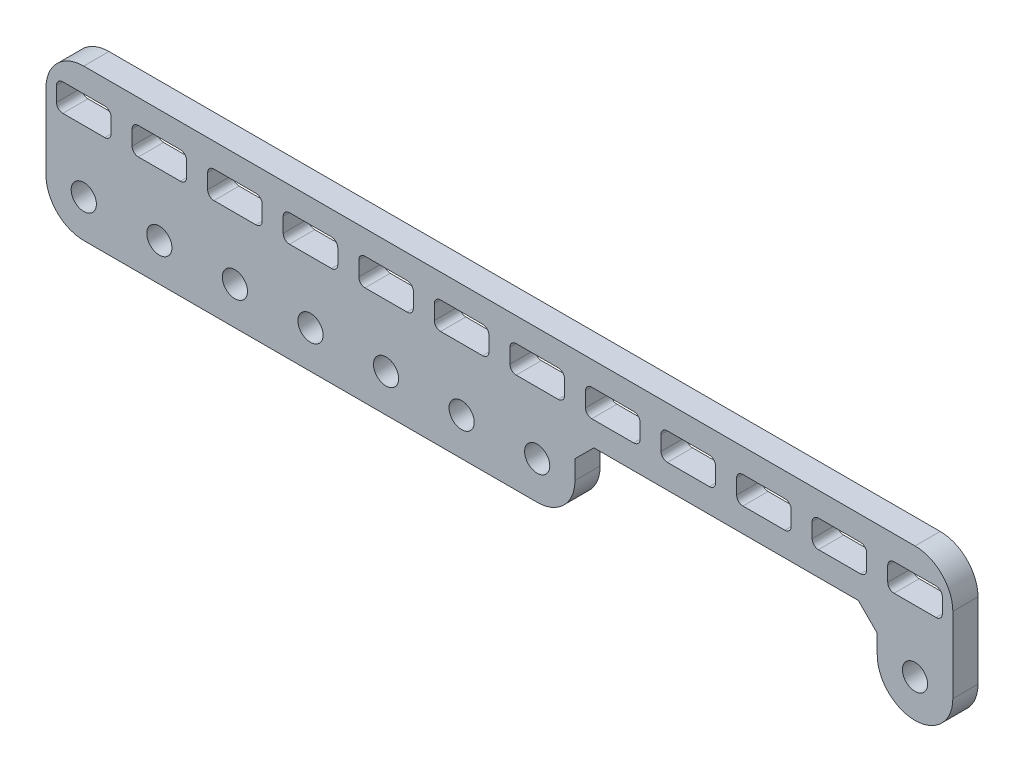
SolidWorks part; units mm, degrees
ref_plane "Alzado" through (0, 0, 0) normal (0, 0, 1) x (1, 0, 0)
ref_plane "Planta" through (0, 0, 0) normal (0, 1, 0) x (1, 0, 0)
ref_plane "Vista lateral" through (0, 0, 0) normal (1, 0, 0) x (0, 0, -1)
sketch "Model" plane through (0, 0, 0) normal (0, 0, 1) x (1, 0, 0)
  line L0 (256.4291, 228.7422) -> (355.4291, 228.7422)
  line L1 (310.4291, 210.7422) -> (256.4291, 210.7422)
  line L2 (359.9291, 224.2422) -> (359.9291, 215.2422)
  line L3 (251.9291, 224.2422) -> (251.9291, 215.2422)
  line L4 (267.9291, 222.6172) -> (262.9291, 222.6172)
  line L5 (262.1791, 223.3672) -> (262.1791, 225.1172)
  line L6 (262.9291, 225.8672) -> (267.9291, 225.8672)
  line L7 (268.6791, 225.1172) -> (268.6791, 223.3672)
  line L8 (285.9291, 222.6172) -> (280.9291, 222.6172)
  line L9 (280.1791, 223.3672) -> (280.1791, 225.1172)
  line L10 (280.9291, 225.8672) -> (285.9291, 225.8672)
  line L11 (286.6791, 225.1172) -> (286.6791, 223.3672)
  line L12 (258.9291, 222.6172) -> (253.9291, 222.6172)
  line L13 (253.1791, 223.3672) -> (253.1791, 225.1172)
  line L14 (253.9291, 225.8672) -> (258.9291, 225.8672)
  line L15 (259.6791, 225.1172) -> (259.6791, 223.3672)
  line L16 (276.9291, 222.6172) -> (271.9291, 222.6172)
  line L17 (271.1791, 223.3672) -> (271.1791, 225.1172)
  line L18 (271.9291, 225.8672) -> (276.9291, 225.8672)
  line L19 (277.6791, 225.1172) -> (277.6791, 223.3672)
  line L20 (294.9291, 222.6172) -> (289.9291, 222.6172)
  line L21 (289.1791, 223.3672) -> (289.1791, 225.1172)
  line L22 (289.9291, 225.8672) -> (294.9291, 225.8672)
  line L23 (295.6791, 225.1172) -> (295.6791, 223.3672)
  line L24 (303.9291, 222.6172) -> (298.9291, 222.6172)
  line L25 (298.1791, 223.3672) -> (298.1791, 225.1172)
  line L26 (298.9291, 225.8672) -> (303.9291, 225.8672)
  line L27 (304.6791, 225.1172) -> (304.6791, 223.3672)
  line L28 (321.9291, 222.6172) -> (316.9291, 222.6172)
  line L29 (316.1791, 223.3672) -> (316.1791, 225.1172)
  line L30 (316.9291, 225.8672) -> (321.9291, 225.8672)
  line L31 (322.6791, 225.1172) -> (322.6791, 223.3672)
  line L32 (312.9291, 222.6172) -> (307.9291, 222.6172)
  line L33 (307.1791, 223.3672) -> (307.1791, 225.1172)
  line L34 (307.9291, 225.8672) -> (312.9291, 225.8672)
  line L35 (313.6791, 225.1172) -> (313.6791, 223.3672)
  line L36 (357.9291, 222.6172) -> (352.9291, 222.6172)
  line L37 (352.1791, 223.3672) -> (352.1791, 225.1172)
  line L38 (352.9291, 225.8672) -> (357.9291, 225.8672)
  line L39 (358.6791, 225.1172) -> (358.6791, 223.3672)
  line L40 (348.9291, 222.6172) -> (343.9291, 222.6172)
  line L41 (343.1791, 223.3672) -> (343.1791, 225.1172)
  line L42 (343.9291, 225.8672) -> (348.9291, 225.8672)
  line L43 (349.6791, 225.1172) -> (349.6791, 223.3672)
  line L44 (339.9291, 222.6172) -> (334.9291, 222.6172)
  line L45 (334.1791, 223.3672) -> (334.1791, 225.1172)
  line L46 (334.9291, 225.8672) -> (339.9291, 225.8672)
  line L47 (340.6791, 225.1172) -> (340.6791, 223.3672)
  line L48 (330.9291, 222.6172) -> (325.9291, 222.6172)
  line L49 (325.1791, 223.3672) -> (325.1791, 225.1172)
  line L50 (325.9291, 225.8672) -> (330.9291, 225.8672)
  line L51 (331.6791, 225.1172) -> (331.6791, 223.3672)
  line L52 (317.1791, 219.7422) -> (348.6791, 219.7422)
  line L53 (314.9291, 215.2422) -> (314.9291, 217.4922)
  line L54 (350.9291, 215.2422) -> (350.9291, 217.4922)
  line L55 (350.9291, 217.4922) -> (348.6791, 219.7422)
  line L56 (314.9291, 217.4922) -> (317.1791, 219.7422)
  arc A0 (359.9291, 224.2422) -> (355.4291, 228.7422) centre (355.4291, 224.2422) ccw
  arc A1 (256.4291, 228.7422) -> (251.9291, 224.2422) centre (256.4291, 224.2422) ccw
  arc A2 (251.9291, 215.2422) -> (256.4291, 210.7422) centre (256.4291, 215.2422) ccw
  circle A3 centre (310.4291, 215.2422) radius 1.5
  circle A4 centre (292.4291, 215.2422) radius 1.5
  circle A5 centre (301.4291, 215.2422) radius 1.5
  circle A6 centre (274.4291, 215.2422) radius 1.5
  circle A7 centre (283.4291, 215.2422) radius 1.5
  circle A8 centre (265.4291, 215.2422) radius 1.5
  circle A9 centre (256.4291, 215.2422) radius 1.5
  circle A10 centre (355.4291, 215.2422) radius 1.5
  arc A11 (262.1791, 223.3672) -> (262.9291, 222.6172) centre (262.9291, 223.3672) ccw
  arc A12 (262.9291, 225.8672) -> (262.1791, 225.1172) centre (262.9291, 225.1172) ccw
  arc A13 (268.6791, 225.1172) -> (267.9291, 225.8672) centre (267.9291, 225.1172) ccw
  arc A14 (267.9291, 222.6172) -> (268.6791, 223.3672) centre (267.9291, 223.3672) ccw
  arc A15 (280.1791, 223.3672) -> (280.9291, 222.6172) centre (280.9291, 223.3672) ccw
  arc A16 (280.9291, 225.8672) -> (280.1791, 225.1172) centre (280.9291, 225.1172) ccw
  arc A17 (286.6791, 225.1172) -> (285.9291, 225.8672) centre (285.9291, 225.1172) ccw
  arc A18 (285.9291, 222.6172) -> (286.6791, 223.3672) centre (285.9291, 223.3672) ccw
  arc A19 (253.1791, 223.3672) -> (253.9291, 222.6172) centre (253.9291, 223.3672) ccw
  arc A20 (253.9291, 225.8672) -> (253.1791, 225.1172) centre (253.9291, 225.1172) ccw
  arc A21 (259.6791, 225.1172) -> (258.9291, 225.8672) centre (258.9291, 225.1172) ccw
  arc A22 (258.9291, 222.6172) -> (259.6791, 223.3672) centre (258.9291, 223.3672) ccw
  arc A23 (271.1791, 223.3672) -> (271.9291, 222.6172) centre (271.9291, 223.3672) ccw
  arc A24 (271.9291, 225.8672) -> (271.1791, 225.1172) centre (271.9291, 225.1172) ccw
  arc A25 (277.6791, 225.1172) -> (276.9291, 225.8672) centre (276.9291, 225.1172) ccw
  arc A26 (276.9291, 222.6172) -> (277.6791, 223.3672) centre (276.9291, 223.3672) ccw
  arc A27 (289.1791, 223.3672) -> (289.9291, 222.6172) centre (289.9291, 223.3672) ccw
  arc A28 (289.9291, 225.8672) -> (289.1791, 225.1172) centre (289.9291, 225.1172) ccw
  arc A29 (295.6791, 225.1172) -> (294.9291, 225.8672) centre (294.9291, 225.1172) ccw
  arc A30 (294.9291, 222.6172) -> (295.6791, 223.3672) centre (294.9291, 223.3672) ccw
  arc A31 (298.1791, 223.3672) -> (298.9291, 222.6172) centre (298.9291, 223.3672) ccw
  arc A32 (298.9291, 225.8672) -> (298.1791, 225.1172) centre (298.9291, 225.1172) ccw
  arc A33 (304.6791, 225.1172) -> (303.9291, 225.8672) centre (303.9291, 225.1172) ccw
  arc A34 (303.9291, 222.6172) -> (304.6791, 223.3672) centre (303.9291, 223.3672) ccw
  arc A35 (316.1791, 223.3672) -> (316.9291, 222.6172) centre (316.9291, 223.3672) ccw
  arc A36 (316.9291, 225.8672) -> (316.1791, 225.1172) centre (316.9291, 225.1172) ccw
  arc A37 (322.6791, 225.1172) -> (321.9291, 225.8672) centre (321.9291, 225.1172) ccw
  arc A38 (321.9291, 222.6172) -> (322.6791, 223.3672) centre (321.9291, 223.3672) ccw
  arc A39 (307.1791, 223.3672) -> (307.9291, 222.6172) centre (307.9291, 223.3672) ccw
  arc A40 (307.9291, 225.8672) -> (307.1791, 225.1172) centre (307.9291, 225.1172) ccw
  arc A41 (313.6791, 225.1172) -> (312.9291, 225.8672) centre (312.9291, 225.1172) ccw
  arc A42 (312.9291, 222.6172) -> (313.6791, 223.3672) centre (312.9291, 223.3672) ccw
  arc A43 (352.1791, 223.3672) -> (352.9291, 222.6172) centre (352.9291, 223.3672) ccw
  arc A44 (352.9291, 225.8672) -> (352.1791, 225.1172) centre (352.9291, 225.1172) ccw
  arc A45 (358.6791, 225.1172) -> (357.9291, 225.8672) centre (357.9291, 225.1172) ccw
  arc A46 (357.9291, 222.6172) -> (358.6791, 223.3672) centre (357.9291, 223.3672) ccw
  arc A47 (343.1791, 223.3672) -> (343.9291, 222.6172) centre (343.9291, 223.3672) ccw
  arc A48 (343.9291, 225.8672) -> (343.1791, 225.1172) centre (343.9291, 225.1172) ccw
  arc A49 (349.6791, 225.1172) -> (348.9291, 225.8672) centre (348.9291, 225.1172) ccw
  arc A50 (348.9291, 222.6172) -> (349.6791, 223.3672) centre (348.9291, 223.3672) ccw
  arc A51 (334.1791, 223.3672) -> (334.9291, 222.6172) centre (334.9291, 223.3672) ccw
  arc A52 (334.9291, 225.8672) -> (334.1791, 225.1172) centre (334.9291, 225.1172) ccw
  arc A53 (340.6791, 225.1172) -> (339.9291, 225.8672) centre (339.9291, 225.1172) ccw
  arc A54 (339.9291, 222.6172) -> (340.6791, 223.3672) centre (339.9291, 223.3672) ccw
  arc A55 (325.1791, 223.3672) -> (325.9291, 222.6172) centre (325.9291, 223.3672) ccw
  arc A56 (325.9291, 225.8672) -> (325.1791, 225.1172) centre (325.9291, 225.1172) ccw
  arc A57 (331.6791, 225.1172) -> (330.9291, 225.8672) centre (330.9291, 225.1172) ccw
  arc A58 (330.9291, 222.6172) -> (331.6791, 223.3672) centre (330.9291, 223.3672) ccw
  arc A59 (310.4291, 210.7422) -> (314.9291, 215.2422) centre (310.4291, 215.2422) ccw
  arc A60 (350.9291, 215.2422) -> (359.9291, 215.2422) centre (355.4291, 215.2422) ccw
extrude "Saliente-Extruir1" add sketch "Model" along normal blind 3
